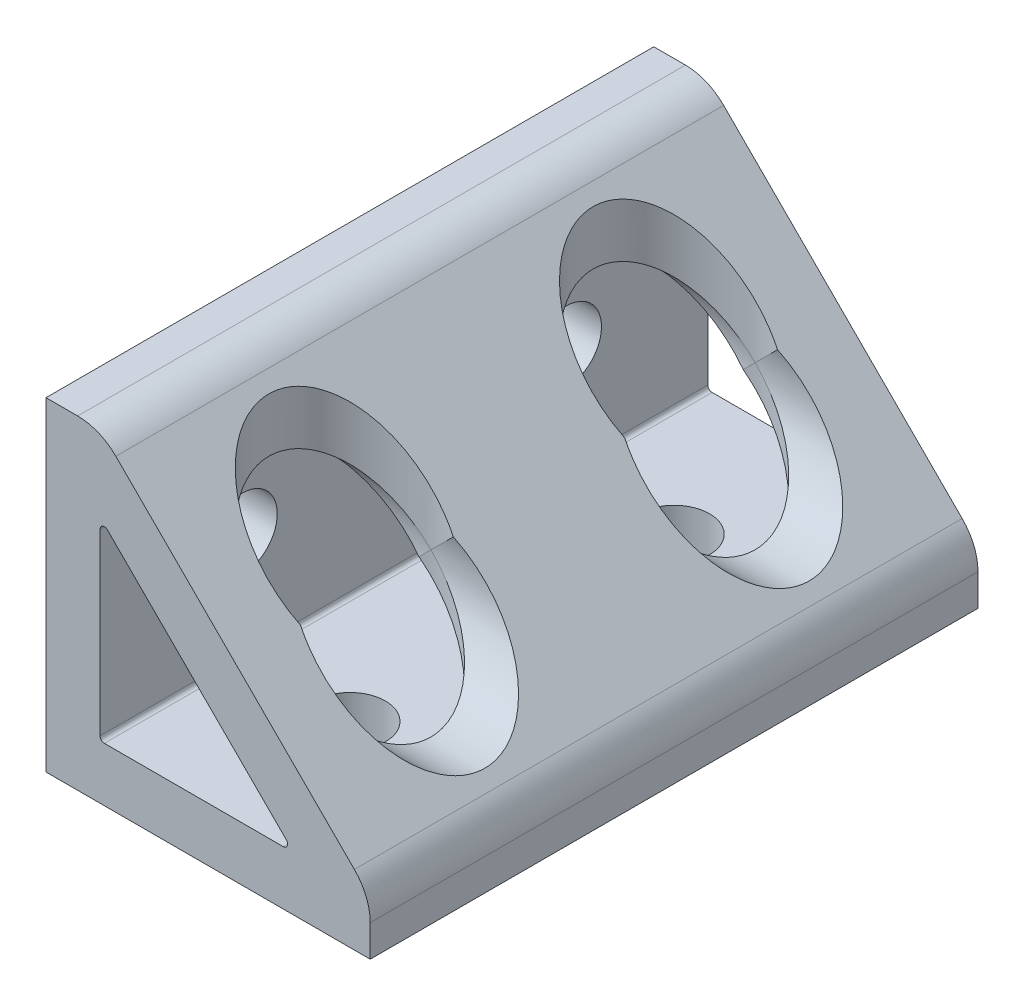
SolidWorks part; units mm, degrees
material "6105-T5 Aluminum"
ref_plane "Front Plane" through (0, 0, 0) normal (0, 0, 1) x (1, 0, 0)
ref_plane "Top Plane" through (0, 0, 0) normal (0, 1, 0) x (1, 0, 0)
ref_plane "Right Plane" through (0, 0, 0) normal (1, 0, 0) x (0, 0, -1)
sketch "Sketch2" plane through (0, 0, 0) normal (0, 0, 1) x (1, 0, 0)
  line L0 (0, 38.1) -> (0, 0)
  line L1 (0, 0) -> (38.1, 0)
  line L2 (38.1, 0) -> (38.1, 3.7197)
  line L3 (8.2099, 36.2401) -> (36.2401, 8.2099)
  line L4 (3.7197, 38.1) -> (0, 38.1)
  line L5 (6.35, 27.8933) -> (6.35, 6.858)
  line L6 (6.858, 6.35) -> (27.8933, 6.35)
  line L7 (7.2172, 28.2525) -> (28.2525, 7.2172)
  line L8 (1.8599, 33.6099) -> (33.6099, 1.8599) construction
  line L9 (6.35, 38.1) -> (38.1, 6.35) construction
  arc A0 (27.8933, 6.35) -> (28.2525, 7.2172) centre (27.8933, 6.858) ccw
  arc A1 (6.35, 27.8933) -> (7.2172, 28.2525) centre (6.858, 27.8933) cw
  arc A2 (6.35, 6.858) -> (6.858, 6.35) centre (6.858, 6.858) ccw
  arc A3 (38.1, 3.7197) -> (36.2401, 8.2099) centre (31.75, 3.7197) ccw
  arc A4 (8.2099, 36.2401) -> (3.7197, 38.1) centre (3.7197, 31.75) ccw
  point P20 (38.1, 6.35)
  dimension "D1" = 6.35
  dimension "D7" = 0.508
  dimension "D8" = 0.508
  dimension "D9" = 6.35
  dimension "D2" = 38.1
  dimension "D3" = 38.1
  dimension "D5" = 6.35
  dimension "D6" = 6.35
extrude "Boss-Extrude2" add sketch "Sketch2" along normal mid plane 71.4248
sketch "Sketch3" plane through (0, 0, 0) normal (-1, 0, 0) x (0, 0, 1)
  line L2 (0, 30.7695) -> (0, 10.6179) construction
  circle A0 centre (19.05, 19.05) radius 4.1656
  circle A1 centre (-19.05, 19.05) radius 4.1656
  dimension "D1" = 8.3312
  dimension "D3" = 19.05
  dimension "D2" = 19.05
extrude "Cut-Extrude1" cut sketch "Sketch3" against normal up to next
sketch "Sketch5" plane through (0, 0, 0) normal (0, -1, 0) x (1, 0, 0)
  line L0 (11.7069, 0) -> (28.7964, 0) construction
  circle A0 centre (19.05, 19.05) radius 4.1656
  circle A1 centre (19.05, -19.05) radius 4.1656
  dimension "D1" = 8.3312
  dimension "D2" = 19.05
  dimension "D3" = 19.05
extrude "Cut-Extrude2" cut sketch "Sketch5" against normal up to next
sketch "Sketch6" plane through (6.35, 0, 0) normal (1, 0, 0) x (0, 0, -1)
  line L0 (0, 31.1565) -> (0, 13.0364) construction
  circle A0 centre (-19.05, 19.05) radius 9.525
  circle A1 centre (19.05, 19.05) radius 9.525
  dimension "D1" = 19.05
extrude "Cut-Extrude3" cut sketch "Sketch6" along normal blind 47.498
sketch "Sketch7" plane through (0, 6.35, 0) normal (0, 1, 0) x (1, 0, 0)
  line L0 (26.8884, 0) -> (10.5575, 0) construction
  circle A0 centre (19.05, 19.05) radius 9.525
  circle A1 centre (19.05, -19.05) radius 9.525
  dimension "D1" = 19.05
extrude "Cut-Extrude4" cut sketch "Sketch7" along normal blind 47.498
